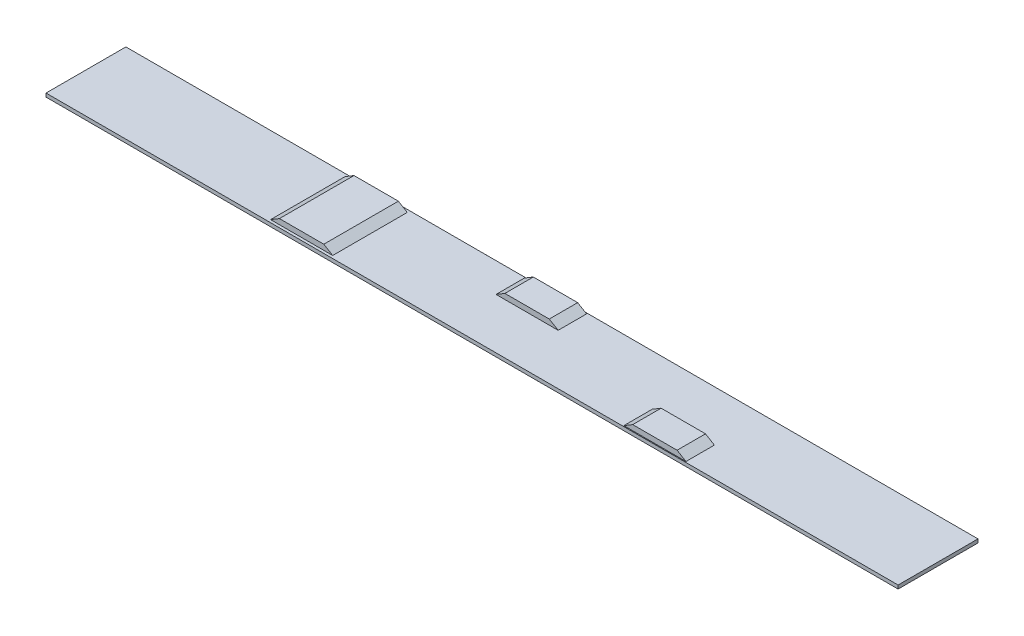
SolidWorks part; units mm, degrees
ref_plane "Front Plane" through (0, 0, 0) normal (0, 0, 1) x (1, 0, 0)
ref_plane "Top Plane" through (0, 0, 0) normal (0, 1, 0) x (1, 0, 0)
ref_plane "Right Plane" through (0, 0, 0) normal (1, 0, 0) x (0, 0, -1)
sketch "Sketch1" plane through (0, 0, 0) normal (0, 1, 0) x (1, 0, 0)
  line L1 (-1200, 112.5) -> (1200, 112.5)
  line L2 (-1200, 112.5) -> (-1200, -112.5)
  line L3 (-1200, -112.5) -> (1200, -112.5)
  line L4 (1200, 112.5) -> (1200, -112.5)
  line L5 (-1200, 112.5) -> (1200, -112.5) construction
  line L6 (-1200, -112.5) -> (1200, 112.5) construction
  point P0 (0, 0)
  dimension "D1" = 2400
  dimension "D2" = 225
extrude "Boss-Extrude1" add sketch "Sketch1" along normal blind 10
sketch "Sketch2" plane through (0, 0, 0) normal (0, 0, 1) x (1, 0, 0)
  line L0 (425, 10) -> (600, 10)
  line L1 (-1200, 10) -> (1200, 10) construction
  line L2 (600, 10) -> (575, 25)
  line L3 (575, 25) -> (450, 25)
  line L4 (450, 25) -> (425, 10)
  line L5 (1200, 10) -> (1200, 0) construction
  point P4 (512.5, 10)
  point P7 (512.5, 25)
  dimension "D1" = 175
  dimension "D2" = 125
  dimension "D3" = 15
  dimension "D4" = 600
extrude "Boss-Extrude2" add sketch "Sketch2" along normal blind 80 from offset 30
sketch "Sketch4" plane through (0, 0, 0) normal (0, 0, 1) x (1, 0, 0)
  line L0 (600, 10) -> (575, 25) construction
  line L1 (425, 10) -> (600, 10) construction
  line L2 (575, 25) -> (450, 25) construction
  line L3 (450, 25) -> (425, 10) construction
  line L4 (600, 10) -> (575, 25) construction
  line L5 (425, 10) -> (600, 10) construction
  line L6 (575, 25) -> (450, 25) construction
  line L7 (450, 25) -> (425, 10) construction
  line L8 (100, 10) -> (75, 25)
  line L9 (75, 25) -> (-50, 25)
  line L10 (-50, 25) -> (-75, 10)
  line L11 (-75, 10) -> (100, 10)
  dimension "D1" = 2
extrude "Boss-Extrude3" add sketch "Sketch4" against normal blind 80 from offset 30 offset against normal yes
sketch "Sketch5" plane through (0, 0, 0) normal (0, 0, 1) x (1, 0, 0)
  line L0 (-575, 10) -> (-400, 10)
  line L1 (-400, 10) -> (-425, 25)
  line L2 (-425, 25) -> (-550, 25)
  line L3 (-550, 25) -> (-575, 10)
  line L4 (-75, 10) -> (100, 10)
  line L5 (100, 10) -> (75, 25)
  line L6 (75, 25) -> (-50, 25)
  line L7 (-50, 25) -> (-75, 10)
  line L8 (-75, 10) -> (100, 10) construction
  line L9 (100, 10) -> (75, 25) construction
  line L10 (75, 25) -> (-50, 25) construction
  line L11 (-50, 25) -> (-75, 10) construction
  dimension "D1" = 0
  dimension "D2" = 2
extrude "Boss-Extrude4" add sketch "Sketch5" along normal blind 105 and the other way blind 105
